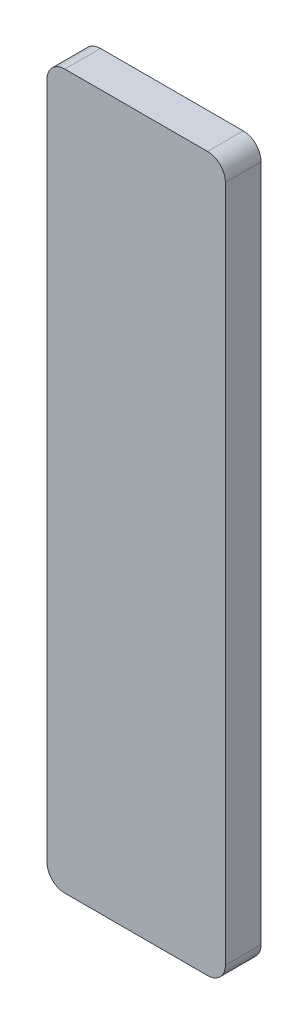
SolidWorks part; units mm, degrees
ref_plane "Front Plane" through (0, 0, 0) normal (0, 0, 1) x (1, 0, 0)
ref_plane "Top Plane" through (0, 0, 0) normal (0, 1, 0) x (1, 0, 0)
ref_plane "Right Plane" through (0, 0, 0) normal (1, 0, 0) x (0, 0, -1)
sketch "Sketch1" plane through (0, 0, 0) normal (0, 0, 1) x (1, 0, 0)
  line L1 (-40, -200) -> (40, -200)
  line L2 (-50, -190) -> (-50, 190)
  line L3 (-40, 200) -> (40, 200)
  line L4 (50, -190) -> (50, 190)
  line L5 (-50, -200) -> (50, 200) construction
  line L6 (-50, 200) -> (50, -200) construction
  arc A0 (40, -200) -> (50, -190) centre (40, -190) ccw
  arc A1 (-40, -200) -> (-50, -190) centre (-40, -190) cw
  arc A2 (-50, 190) -> (-40, 200) centre (-40, 190) cw
  arc A3 (40, 200) -> (50, 190) centre (40, 190) cw
  point P0 (0, 0)
  dimension "D3" = 10
  dimension "D1" = 100
  dimension "D2" = 400
extrude "Boss-Extrude1" add sketch "Sketch1" along normal blind 20
